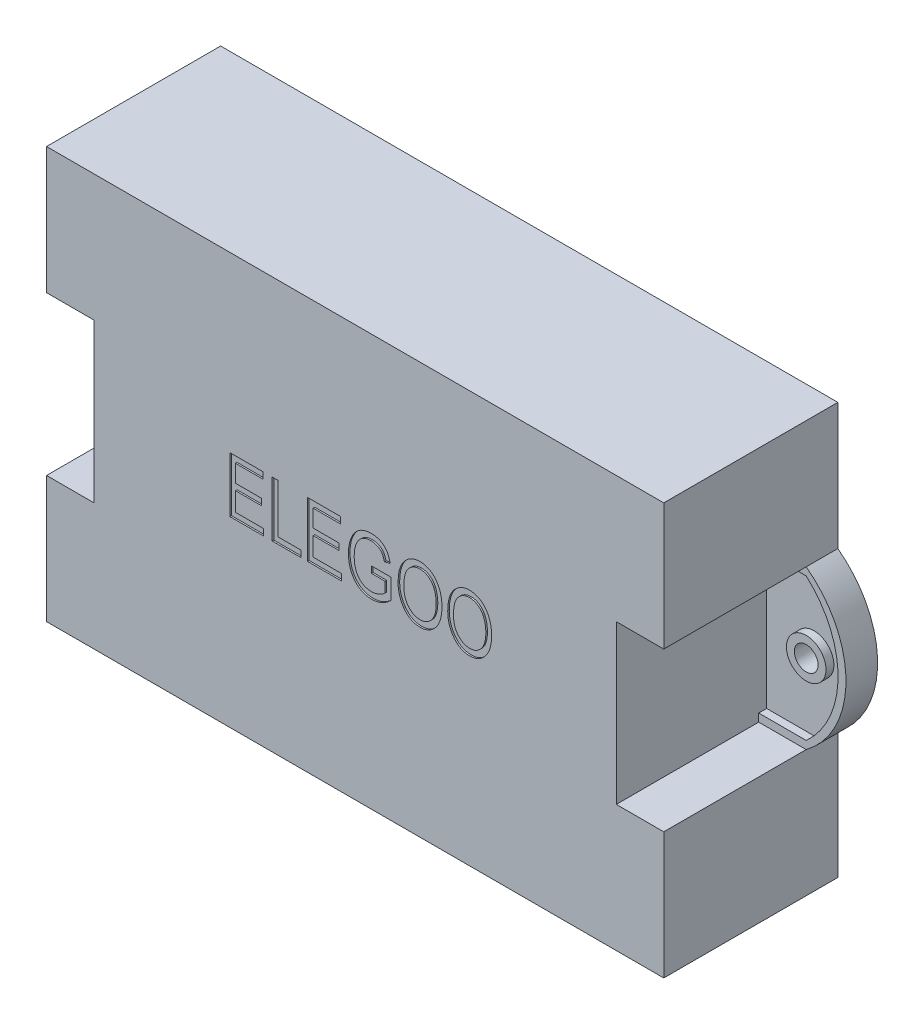
SolidWorks part; units mm, degrees
ref_plane "Plan de face" through (0, 0, 0) normal (0, 0, 1) x (1, 0, 0)
ref_plane "Plan de dessus" through (0, 0, 0) normal (0, 1, 0) x (1, 0, 0)
ref_plane "Plan de droite" through (0, 0, 0) normal (1, 0, 0) x (0, 0, -1)
sketch "Esquisse1" plane through (0, 0, 0) normal (0, 0, 1) x (1, 0, 0)
  line L1 (-2.21, 17.03) -> (36.79, 17.03)
  line L2 (-2.21, 17.03) -> (-2.21, -34.97)
  line L3 (-2.21, -34.97) -> (36.79, -34.97)
  line L5 (36.79, 17.03) -> (36.79, 1.03)
  line L10 (36.79, -18.97) -> (36.79, -34.97)
  arc A0 (36.79, 1.03) -> (36.79, -18.97) centre (29.3491, -8.97) cw
  dimension "D1" = 39
  dimension "D2" = 52
extrude "Boss.-Extru.1" add sketch "Esquisse1" along normal blind 3
sketch "Esquisse2" plane through (0, 0, 3) normal (0, 0, 1) x (1, 0, 0)
  line L0 (36.79, 1.03) -> (30.79, 1.03)
  line L1 (-2.21, 17.03) -> (36.79, 17.03)
  line L2 (-2.21, 17.03) -> (-2.21, -34.97)
  line L3 (-2.21, -34.97) -> (36.79, -34.97)
  line L4 (36.79, 17.03) -> (36.79, -34.97)
  line L5 (36.79, -18.97) -> (30.79, -18.97)
  line L6 (30.79, -18.97) -> (30.79, 1.03)
  line M6 (-2.21, 17.03) -> (-2.21, -34.97)
  line M7 (-2.21, -34.97) -> (36.79, -34.97)
  line M8 (36.79, -34.97) -> (36.79, -18.97)
  line M10 (36.79, 1.03) -> (36.79, 17.03)
  line M11 (36.79, 17.03) -> (-2.21, 17.03)
extrude "Boss.-Extru.2" add sketch "Esquisse2" along normal blind 19 contours L5 L6 L0 M10 M11 M6 M7 M8
sketch "Esquisse3" plane through (0, 0, 3) normal (0, 0, 1) x (1, 0, 0)
  line L1 (36.79, -18.97) -> (30.79, -18.97) construction
  line L2 (36.79, 1.03) -> (30.79, 1.03) construction
  line L3 (36.79, 0.03) -> (30.79, 0.03)
  line L7 (35.5044, 1.03) -> (36.79, 1.03)
  line L8 (36.79, -18.97) -> (35.5074, -18.97)
  line L9 (30.79, -18.97) -> (30.79, 1.03) construction
  line L10 (30.79, 0.03) -> (30.79, 1.03)
  line L11 (30.79, 1.03) -> (35.5044, 1.03)
  line L12 (36.79, -17.97) -> (30.79, -17.97)
  line L13 (30.79, -17.97) -> (30.79, -18.97)
  line L14 (30.79, -18.97) -> (35.5074, -18.97)
  circle A0 centre (36.79, -8.97) radius 1.5
  circle A1 centre (36.79, -8.97) radius 2.5
  arc A3 (36.79, 0.03) -> (36.79, -17.97) centre (28.7416, -8.97) cw
  arc A5 (36.79, 0.03) -> (35.5074, -18.97) centre (28.7416, -8.97) cw
  arc A6 (40.8137, -8.97) -> (35.5044, 1.03) centre (28.7416, -8.97) ccw
  arc A7 (36.79, 1.03) -> (36.79, -18.97) centre (29.3491, -8.97) cw
  line M7 (30.79, -18.97) -> (36.79, -18.97)
  arc M8 (36.79, -18.97) -> (36.79, 1.03) centre (29.3491, -8.97) ccw
  line M9 (36.79, 1.03) -> (30.79, 1.03)
  line M10 (30.79, 1.03) -> (30.79, -18.97)
extrude "Boss.-Extru.9" add sketch "Esquisse3" along normal blind 1 contours A1 A0 | A6 L3 A3 A5 M7 M8 M9 | L3 A6 M9 M10 | A5 L12 M10 M7
mirror "Symétrie6" about plane through (-2.21, 17.03, 3) normal (1, 0, 0) of "Boss.-Extru.9", "Boss.-Extru.1", "Boss.-Extru.2"
sketch "Esquisse5" plane through (0, 0, 22) normal (0, 0, 1) x (1, 0, 0)
  text T0 "ELEGOO" font "Arial Narrow" height 7
extrude "Enlèv. mat.-Extru.2" cut sketch "Esquisse5" against normal blind 0.2
sketch "Esquisse6" plane through (0, 0, 3) normal (0, 0, 1) x (1, 0, 0)
  line L0 (-2.21, 17.03) -> (-2.21, -34.97) construction
  circle A0 centre (36.79, -8.97) radius 1.5
  circle A1 centre (-41.21, -8.97) radius 1.5
extrude "Enlèv. mat.-Extru.3" cut sketch "Esquisse6" against normal blind 10
sketch "Sketch1" plane through (0, 0, 0) normal (0, 0, -1) x (-1, 0, 0)
  line L0 (-36.79, 17.03) -> (-36.79, 1.03)
  line L1 (-36.79, 17.03) -> (41.21, 17.03)
  line L2 (41.21, 17.03) -> (41.21, 1.03)
  line L3 (41.21, -18.97) -> (41.21, -34.97)
  line L4 (41.21, -34.97) -> (-36.79, -34.97)
  line L5 (-36.79, -34.97) -> (-36.79, -18.97)
  arc A0 (-36.79, -18.97) -> (-36.79, 1.03) centre (-29.3491, -8.97) cw
  arc A1 (41.21, -18.97) -> (41.21, 1.03) centre (33.7691, -8.97) ccw
  circle A2 centre (-36.79, -8.97) radius 1.5
  circle A3 centre (41.21, -8.97) radius 1.5
